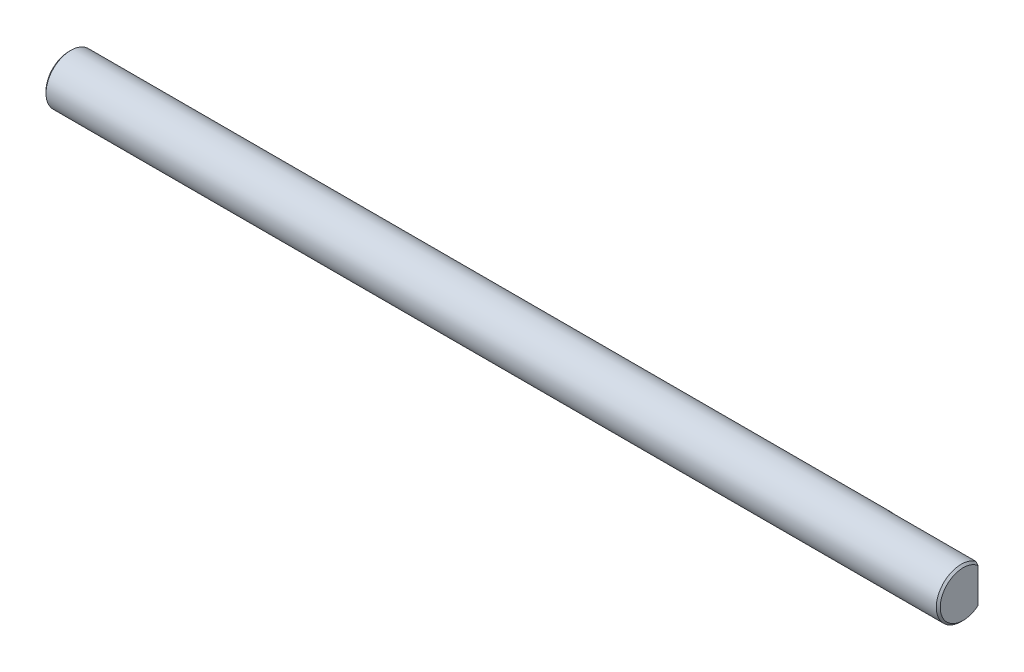
SolidWorks part; units mm, degrees
ref_plane "Front Plane" through (0, 0, 0) normal (0, 0, 1) x (1, 0, 0)
ref_plane "Top Plane" through (0, 0, 0) normal (0, 1, 0) x (1, 0, 0)
ref_plane "Right Plane" through (0, 0, 0) normal (1, 0, 0) x (0, 0, -1)
sketch "Sketch1" plane through (0, 0, 0) normal (0, 1, 0) x (1, 0, 0)
  line L1 (0, 0) -> (-90, 0)
  line L2 (0, 0) -> (0, 2.5)
  line L3 (0, 2.5) -> (-90, 2.5)
  line L4 (-90, 0) -> (-90, 2.5)
  dimension "D1" = 90
  dimension "D2" = 2.5
revolve "Revolve1" add sketch "Sketch1" angle 360 about L1
sketch "Sketch2" plane through (0, 0, 0) normal (0, 1, 0) x (1, 0, 0)
  line L0 (0, 1.5) -> (-9, 1.5)
  line L1 (0, -2.5) -> (0, 2.5) construction
  line L2 (-9, 1.5) -> (-9, 2.5)
  line L3 (0, 2.5) -> (-90, 2.5) construction
  line L4 (-9, 2.5) -> (0, 2.5)
  line L5 (0, 2.5) -> (0, 1.5)
  dimension "D1" = 9
  dimension "D2" = 1.5
extrude "Cut-Extrude1" cut sketch "Sketch2" against normal through all both and the other way through all
chamfer "Chamfer1" distance 0.2 angle 45 2 edges at (0, 0, 2.5) (-90, 0, -2.5)
